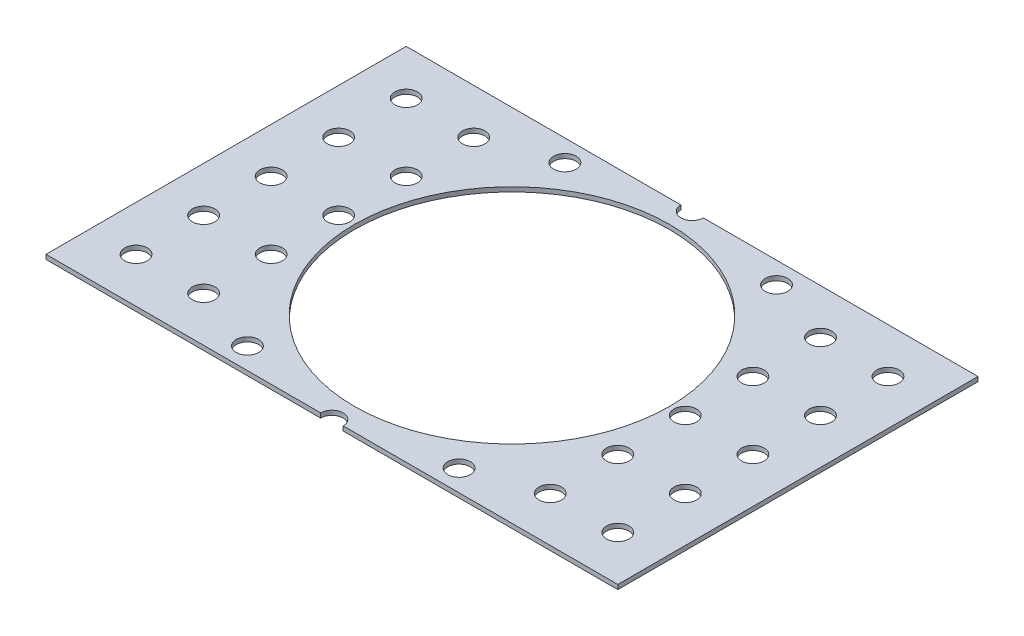
SolidWorks part; units mm, degrees
ref_plane "Front Plane" through (0, 0, 0) normal (0, 0, 1) x (1, 0, 0)
ref_plane "Top Plane" through (0, 0, 0) normal (0, 1, 0) x (1, 0, 0)
ref_plane "Right Plane" through (0, 0, 0) normal (1, 0, 0) x (0, 0, -1)
sketch "Sketch1" plane through (0, 0, 0) normal (0, 1, 0) x (1, 0, 0)
  line L0 (-56.0828, 25) -> (-56.0828, -55) construction
  line L1 (-66.0828, 25) -> (-5.0828, 25)
  line L2 (-66.0828, 25) -> (-66.0828, -55)
  line L3 (-66.0828, -55) -> (-5.0828, -55)
  line L4 (60.9172, 25) -> (60.9172, -55)
  line L5 (-41.0828, 25) -> (-41.0828, -55) construction
  line L6 (-2.5828, 25) -> (-2.5828, -55) construction
  line L7 (-26.0828, 25) -> (-26.0828, -55) construction
  line L8 (-66.0828, 15) -> (60.9172, 15) construction
  line L9 (-66.0828, 0) -> (60.9172, 0) construction
  line L10 (-66.0828, -15) -> (60.9172, -15) construction
  line L11 (-0.0828, -55) -> (60.9172, -55)
  line L12 (-0.0828, 25) -> (60.9172, 25)
  line L19 (33.8718, 23.2019) -> (33.8718, -58.6976) construction
  circle A0 centre (-2.5828, -15) radius 35
  circle A1 centre (-56.0828, 15) radius 2.5
  circle A2 centre (-41.0828, 15) radius 2.5
  circle A3 centre (-56.0828, 0) radius 2.5
  circle A4 centre (-41.0828, 0) radius 2.5
  circle A5 centre (-26.0828, 20.2529) radius 2.5
  circle A6 centre (-56.0828, -15) radius 2.5
  circle A7 centre (-41.0828, -15) radius 2.5
  arc A8 (-5.0828, 25) -> (-0.0828, 25) centre (-2.5828, 25.0209) ccw
  circle A9 centre (50.9172, 15) radius 2.5
  circle A10 centre (50.9172, 0) radius 2.5
  circle A11 centre (50.9172, -15) radius 2.5
  circle A12 centre (35.9172, -15) radius 2.5
  circle A13 centre (35.9172, 0) radius 2.5
  circle A14 centre (35.9172, 15) radius 2.5
  circle A15 centre (20.9172, 20.2529) radius 2.5
  circle A17 centre (-26.0828, -50.2529) radius 2.5
  circle A18 centre (-41.0828, -45) radius 2.5
  circle A19 centre (-41.0828, -30) radius 2.5
  circle A20 centre (-56.0828, -30) radius 2.5
  circle A21 centre (-56.0828, -45) radius 2.5
  circle A22 centre (50.9172, -45) radius 2.5
  circle A23 centre (50.9172, -30) radius 2.5
  circle A24 centre (35.9172, -30) radius 2.5
  circle A25 centre (35.9172, -45) radius 2.5
  circle A26 centre (20.9172, -50.2529) radius 2.5
  arc A27 (-5.0828, -55) -> (-0.0828, -55) centre (-2.5828, -55) cw
  dimension "D3" = 70
  dimension "D5" = 15
  dimension "D6" = 15
  dimension "D4" = 10
  dimension "D9" = 5
  dimension "D1" = 127
  dimension "D2" = 80
  dimension "D8" = 15
extrude "Boss-Extrude1" add sketch "Sketch1" along normal blind 1
